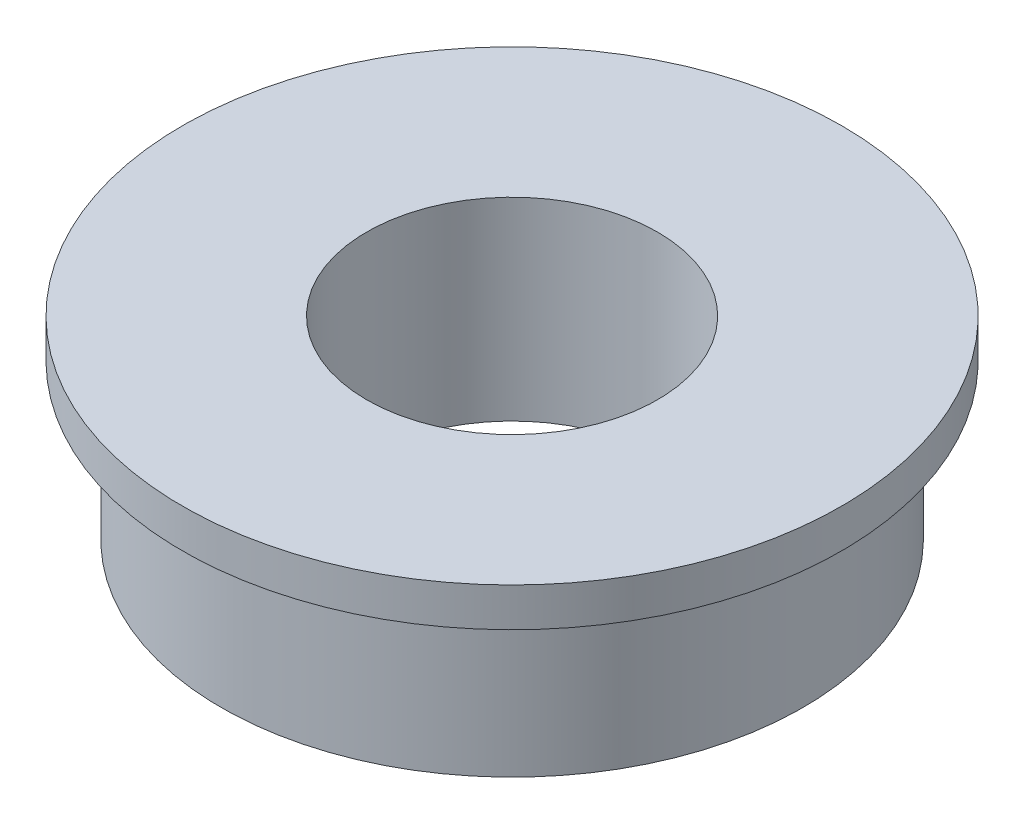
SolidWorks part; units mm, degrees
ref_plane "Piano frontale" through (0, 0, 0) normal (0, 0, 1) x (1, 0, 0)
ref_plane "Piano superiore" through (0, 0, 0) normal (0, 1, 0) x (1, 0, 0)
ref_plane "Piano destro" through (0, 0, 0) normal (1, 0, 0) x (0, 0, -1)
sketch "Schizzo1" plane through (0, 0, 0) normal (0, 0, 1) x (1, 0, 0)
  line L0 (0, 0) -> (0, 18.5042) construction
  line L1 (3, 4) -> (3, 0)
  line L2 (3, 0) -> (6, 0)
  line L3 (6, 0) -> (6, 3.2)
  line L4 (6, 3.2) -> (6.8, 3.2)
  line L5 (6.8, 3.2) -> (6.8, 4)
  line L6 (6.8, 4) -> (3, 4)
  dimension "D1" = 12
  dimension "D2" = 0.8
  dimension "D3" = 6
  dimension "D4" = 4
  dimension "D5" = 13.6
revolve "Rivoluzione1" add sketch "Schizzo1" angle 360 about L0
